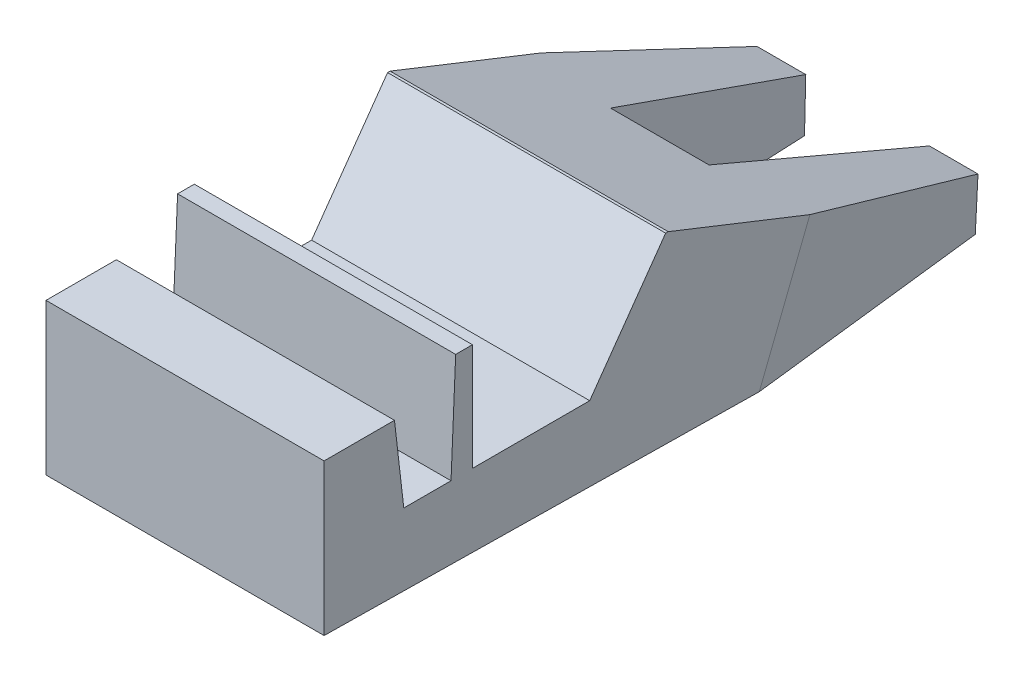
SolidWorks part; units mm, degrees
ref_plane "Спереди" through (0, 0, 0) normal (0, 0, 1) x (1, 0, 0)
ref_plane "Сверху" through (0, 0, 0) normal (0, 1, 0) x (1, 0, 0)
ref_plane "Справа" through (0, 0, 0) normal (1, 0, 0) x (0, 0, -1)
other "Графика1"
other "Графика (Открыто) -1"
sketch "Эскиз1" plane through (0, 0, 0) normal (0, 1, 0) x (1, 0, 0)
  line L0 (34.8087, 483.4719) -> (160.1995, 483.4719) construction
  line L1 (160.1995, 483.4719) -> (384.1306, 483.4719) construction
  line L2 (34.8087, 483.4719) -> (0, 483.4719) construction
  line L3 (97.5041, 4.4625) -> (97.5041, 313.9247) construction
  line L4 (97.5041, 313.9247) -> (97.5041, 483.4719) construction
  line L5 (97.5041, 4.4625) -> (384.1306, 4.4625) construction
  line L6 (97.5041, 4.4625) -> (0, 4.4625) construction
  line L7 (0, 4.4625) -> (0, 483.4719) construction
  line L8 (195.0083, 4.4625) -> (195.0083, 483.4719) construction
  line L10 (0, 483.4719) -> (195.0083, 483.4719)
  line L11 (0, 483.4719) -> (0, 4.4625)
  line L12 (0, 4.4625) -> (195.0083, 4.4625)
  line L13 (195.0083, 483.4719) -> (195.0083, 4.4625)
  point P11 (3.8898, 288.268)
extrude "Бобышка-Вытянуть2" add sketch "Эскиз1" along normal blind 135 contours L12 L13 L10 L11
sketch "Эскиз2" plane through (0, 0, -4.4625) normal (0, 0, 1) x (1, 0, 0)
  line L1 (0, 0) -> (195.0083, 0)
  line L2 (0, 0) -> (0, 135)
  line L3 (0, 135) -> (195.0083, 135)
  line L4 (195.0083, 0) -> (195.0083, 135)
sketch "Эскиз3" plane through (0, 0, 0) normal (-1, 0, 0) x (0, 0, 1)
  line L0 (-245.7605, 135) -> (-483.4719, 40.9372)
  line L1 (-483.4719, 135) -> (-4.4625, 135)
  line L2 (-483.4719, 135) -> (-483.4719, 0)
  line L3 (-483.4719, 0) -> (-4.4625, 0)
  line L4 (-4.4625, 135) -> (-4.4625, 0)
  line L5 (-243.9672, 135) -> (-190.7178, 59.8869)
  line L6 (-190.7178, 59.8869) -> (-108.4747, 59.8869)
  line L7 (-108.4747, 135) -> (-108.4747, 59.8869)
  line L8 (-96.7315, 135) -> (-93.4633, 59.8869)
  line L9 (-93.4633, 59.8869) -> (-60.3452, 59.8869)
  line L10 (-60.3452, 59.8869) -> (-53.8087, 116.4356)
  line L11 (-53.8087, 116.4356) -> (-4.4625, 116.4356)
  line L12 (-4.4625, 10.364) -> (-483.4719, 3.306)
  line M1 (-483.4719, 0) -> (-4.4625, 0)
  line M2 (-4.4625, 0) -> (-4.4625, 135)
  line M3 (-4.4625, 135) -> (-483.4719, 135)
  line M4 (-483.4719, 135) -> (-483.4719, 0)
extrude "Вырез-Вытянуть4" cut sketch "Эскиз3" against normal blind 200 contours L0 M3 M4 | L7 L1 L5 L6 | L10 L11 L4 L8 L9 M3 | L12 L2 M2 M1
sketch "Эскиз4" plane through (0, 200.8057, -79.4592) normal (0, 0.9298, -0.3679) x (1, 0, 0)
  line L0 (195.0083, 285.7268) -> (174.4774, 434.8758)
  line L1 (0, 434.493) -> (195.0083, 434.493)
  line L2 (0, 434.493) -> (0, 178.8478)
  line L3 (0, 178.8478) -> (195.0083, 178.8478)
  line L4 (195.0083, 434.493) -> (195.0083, 178.8478)
  line L5 (19.6037, 434.493) -> (0, 292.915)
  line L6 (140.4552, 434.493) -> (132.8961, 276.4235)
  line L7 (53.7476, 434.493) -> (63.822, 276.4235)
  line L8 (63.822, 276.4235) -> (132.8961, 276.4235)
  line L9 (0, 434.493) -> (0, 491.2678)
  line L10 (0, 491.2678) -> (195.0083, 491.2678)
  line L11 (195.0083, 491.2678) -> (195.0083, 434.493)
  line L12 (19.6037, 434.493) -> (27.4651, 491.2678)
  line L13 (174.4774, 434.8758) -> (166.7149, 491.2678)
  line L14 (53.7476, 434.493) -> (50.1291, 491.2678)
  line L15 (140.4552, 434.493) -> (143.1702, 491.2678)
  line M1 (195.0083, 434.493) -> (0, 434.493)
  line M2 (0, 434.493) -> (0, 178.8478)
  line M4 (195.0083, 178.8478) -> (195.0083, 434.493)
extrude "Вырез-Вытянуть23" cut sketch "Эскиз4" against normal blind 200 contours L1 L15 L10 L14 | L7 L8 L6 L1 | L1 L12 L10 L9 | L5 L1 M2 | L0 M4 M1 | L13 L0 L11 L10 M1
sketch "Эскиз9" plane through (0, 0, -108.4747) normal (0, 0, -1) x (-1, 0, 0)
sketch "Эскиз10" plane through (0, 200.8057, -79.4592) normal (0, 0.9298, -0.3679) x (1, 0, 0)
  line L0 (0, 292.915) -> (19.6037, 434.493)
  line L1 (0, 177.1802) -> (195.0083, 177.1802)
  line L2 (0, 177.1802) -> (0, 449.5556)
  line L4 (195.0083, 177.1802) -> (195.0083, 285.7268)
  line L5 (19.6037, 434.493) -> (53.7476, 434.493)
  line L6 (53.7476, 434.493) -> (63.822, 276.4235)
  line L7 (63.822, 276.4235) -> (132.8961, 276.4235)
  line L8 (132.8961, 276.4235) -> (140.4552, 434.493)
  line L9 (140.4552, 434.493) -> (174.5301, 434.493)
  line L10 (174.5301, 434.493) -> (195.0083, 285.7268)
  line L11 (195.0083, 285.7268) -> (195.0083, 177.1802)
